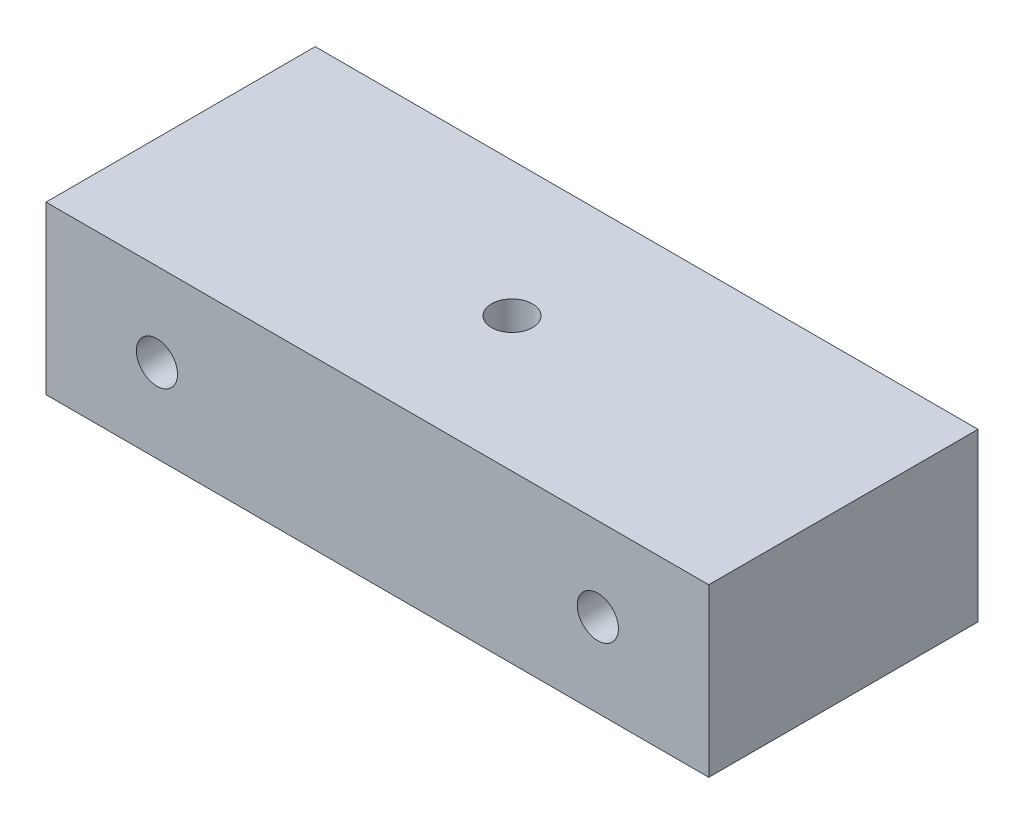
SolidWorks part; units mm, degrees
ref_plane "Front Plane" through (0, 0, 0) normal (0, 0, 1) x (1, 0, 0)
ref_plane "Top Plane" through (0, 0, 0) normal (0, 1, 0) x (1, 0, 0)
ref_plane "Right Plane" through (0, 0, 0) normal (1, 0, 0) x (0, 0, -1)
sketch "Sketch1" plane through (0, 0, 0) normal (0, 0, 1) x (1, 0, 0)
  line L1 (60.6717, -154.0174) -> (35.5217, -154.0174) construction
  line L3 (60.6717, -154.0174) -> (15.5717, -154.0174) construction
  line L4 (60.6717, -154.0174) -> (60.6717, -144.1674)
  line L5 (60.6717, -144.1674) -> (15.5717, -144.1674)
  line L6 (15.5717, -154.0174) -> (15.5717, -144.1674)
  line L7 (60.6717, -154.0174) -> (15.5717, -144.1674) construction
  line L8 (60.6717, -144.1674) -> (15.5717, -154.0174) construction
  line L11 (15.5717, -154.0174) -> (15.5717, -155.5174)
  line L12 (15.5717, -155.5174) -> (60.6717, -155.5174)
  line L14 (60.6717, -155.5174) -> (60.6717, -154.0174)
  point P5 (38.1217, -149.0924)
  dimension "D2" = 1.5
extrude "Boss-Extrude1" add sketch "Sketch1" along normal up to surface (18.32 mm away) from offset 0.05 contours L4 L5 L6 L11 L12 L14
sketch "Sketch2" plane through (0, 0, 18.37) normal (0, 0, 1) x (1, 0, 0)
  line L0 (15.5717, -149.8424) -> (60.6717, -149.8424) construction
  line L1 (15.5717, -155.5174) -> (15.5717, -144.1674) construction
  line L2 (60.6717, -155.5174) -> (60.6717, -144.1674) construction
  line L3 (23.1217, -148.4424) -> (53.1217, -148.4424) construction
  circle A0 centre (23.1217, -149.8424) radius 1.4
  circle A1 centre (53.1217, -149.8424) radius 1.4
  point P12 (38.1217, -148.4424)
  point P14 (38.1217, -149.8424)
  dimension "D1" = 30
  dimension "D2" = 2.8
extrude "Cut-Extrude1" cut sketch "Sketch2" against normal through all both and the other way through all
sketch "Sketch3" plane through (0, -144.1674, 0) normal (0, 1, 0) x (1, 0, 0)
  circle A1 centre (38.1217, -9.21) radius 1.4
extrude "Cut-Extrude2" cut sketch "Sketch3" against normal through all
